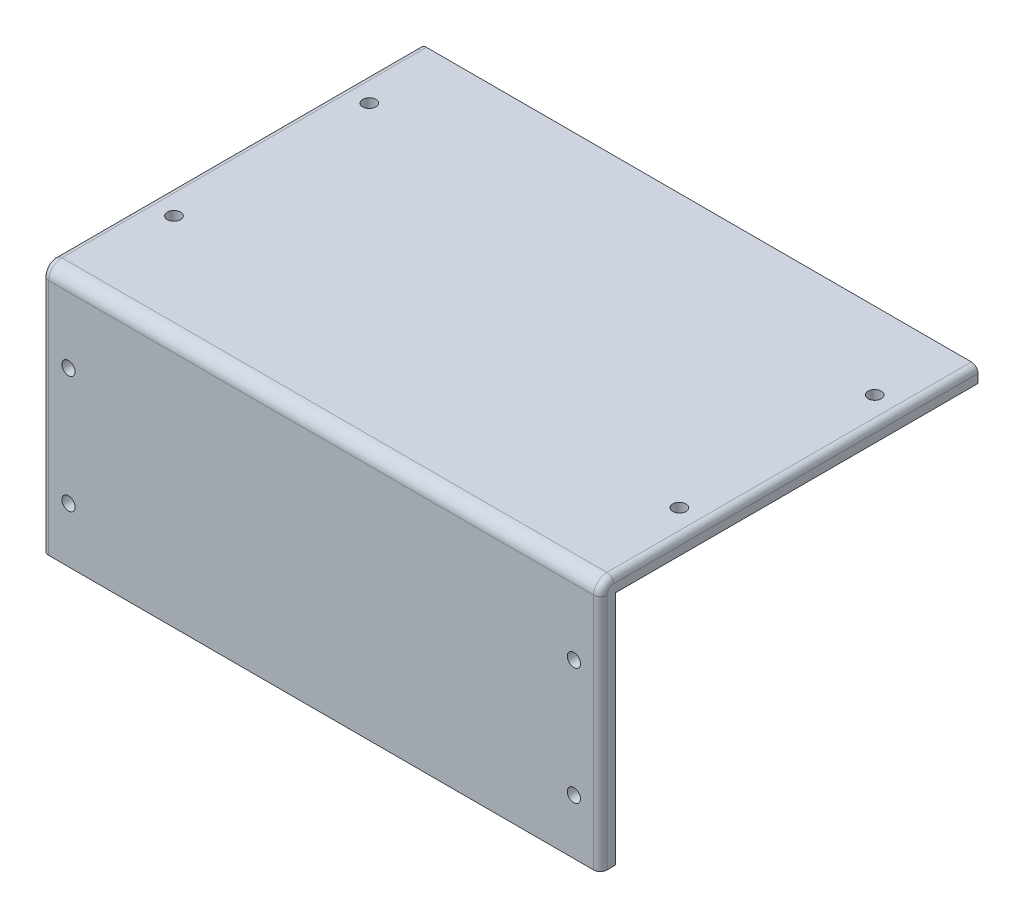
SolidWorks part; units mm, degrees
ref_plane "Front Plane" through (0, 0, 0) normal (0, 0, 1) x (1, 0, 0)
ref_plane "Top Plane" through (0, 0, 0) normal (0, 1, 0) x (1, 0, 0)
ref_plane "Right Plane" through (0, 0, 0) normal (1, 0, 0) x (0, 0, -1)
sketch "Sketch1" plane through (0, 0, 0) normal (0, 0, 1) x (1, 0, 0)
  line L1 (0, 0) -> (127, 0)
  line L2 (0, 0) -> (0, 53.65)
  line L3 (0, 53.65) -> (127, 53.65)
  line L4 (127, 0) -> (127, 53.65)
  dimension "D1" = 127
  dimension "D2" = 53.65
extrude "Boss-Extrude1" add sketch "Sketch1" along normal blind 3.5
sketch "Sketch2" plane through (0, 0, 0) normal (-1, 0, 0) x (0, 0, 1)
  line L0 (3.5, 53.65) -> (3.5, 54.15)
  line L1 (0.5, 57.15) -> (-82.44, 57.15)
  line L2 (-82.44, 57.15) -> (-82.44, 53.65)
  line L3 (-82.44, 53.65) -> (0, 53.65)
  line L4 (0, 53.65) -> (3.5, 53.65)
  arc A0 (3.5, 54.15) -> (0.5, 57.15) centre (0.5, 54.15) ccw
  dimension "D2" = 82.44
  dimension "D1" = 3.5
extrude "Boss-Extrude3" add sketch "Sketch2" against normal blind 127
sketch "Sketch4" plane through (0, 0, 0) normal (0, 0, -1) x (-1, 0, 0)
  line L0 (-63.5, 75.5817) -> (-63.5, -14.2444) construction
  line L1 (-127, 0) -> (-127, 53.65) construction
  line L2 (-127, 53.65) -> (0, 53.65) construction
  line L3 (0, 0) -> (-127, 0) construction
  circle A0 centre (-121, 39.15) radius 1.5
  circle A1 centre (-121, 12.5) radius 1.5
  circle A2 centre (-6, 12.5) radius 1.5
  circle A3 centre (-6, 39.15) radius 1.5
  dimension "D2" = 3
  dimension "D3" = 3
  dimension "D1" = 63.5
  dimension "D4" = 6
  dimension "D5" = 6
  dimension "D6" = 14.5
  dimension "D7" = 12.5
extrude "Cut-Extrude1" cut sketch "Sketch4" against normal blind 3.5
sketch "Sketch6" plane through (0, 53.65, 0) normal (0, -1, 0) x (1, 0, 0)
  line L0 (0, -82.44) -> (0, 0) construction
  line L1 (127, 0) -> (0, 0) construction
  line L2 (127, -82.44) -> (0, -82.44) construction
  line L3 (63.5, 9.0361) -> (63.5, -91.84) construction
  circle A0 centre (6, -20.5) radius 1.5
  circle A1 centre (6, -64.94) radius 1.5
  circle A2 centre (121, -64.94) radius 1.5
  circle A3 centre (121, -20.5) radius 1.5
  dimension "D1" = 3
  dimension "D2" = 3
  dimension "D3" = 6
  dimension "D4" = 6
  dimension "D5" = 20.5
  dimension "D6" = 17.5
  dimension "D7" = 63.5
extrude "Cut-Extrude3" cut sketch "Sketch6" against normal blind 3.5
fillet "Fillet1" radius 1.5 3 edges at (127, 57.15, -40.97) (127, 56.2713, 2.6213) (127, 27.075, 3.5)
fillet "Fillet2" radius 1.5 3 edges at (0, 57.15, -40.97) (0, 56.2713, 2.6213) (0, 27.075, 3.5)
